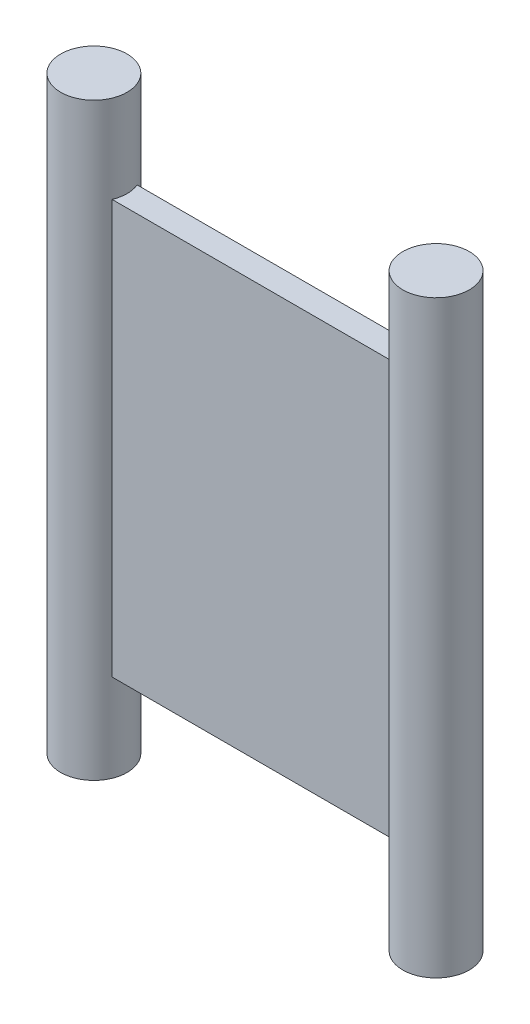
SolidWorks part; units mm, degrees
ref_plane "Front Plane" through (0, 0, 0) normal (0, 0, 1) x (1, 0, 0)
ref_plane "Top Plane" through (0, 0, 0) normal (0, 1, 0) x (1, 0, 0)
ref_plane "Right Plane" through (0, 0, 0) normal (1, 0, 0) x (0, 0, -1)
sketch "Sketch1" plane through (0, 0, 0) normal (0, 1, 0) x (1, 0, 0)
  line L1 (6.825, 0.5) -> (-6.825, 0.5)
  line L2 (6.825, 0.5) -> (6.825, -0.5)
  line L3 (6.825, -0.5) -> (-6.825, -0.5)
  line L4 (-6.825, 0.5) -> (-6.825, -0.5)
  line L5 (6.825, 0.5) -> (-6.825, -0.5) construction
  line L6 (6.825, -0.5) -> (-6.825, 0.5) construction
  point P0 (0, 0)
  dimension "D1" = 13.65
  dimension "D3" = 1
extrude "Boss-Extrude1" add sketch "Sketch1" along normal blind 16.5
ref_plane "Plane1" through (0, 8.25, 0) normal (0, 1, 0) x (1, 0, 0)
sketch "Sketch2" plane through (0, 8.25, 0) normal (0, 1, 0) x (1, 0, 0)
  line L0 (6.825, -0.5) -> (6.825, 0.5) construction
  line L1 (-6.825, 0.5) -> (-6.825, -0.5) construction
  line L2 (6.825, -0.5) -> (6.825, 0.5) construction
  line L3 (-6.825, 0.5) -> (-6.825, -0.5) construction
  circle A0 centre (-6.825, 0) radius 1.325
  circle A1 centre (6.825, 0) radius 1.325
  dimension "D1" = 2.65
extrude "Boss-Extrude2" add sketch "Sketch2" along normal mid plane 23.5
